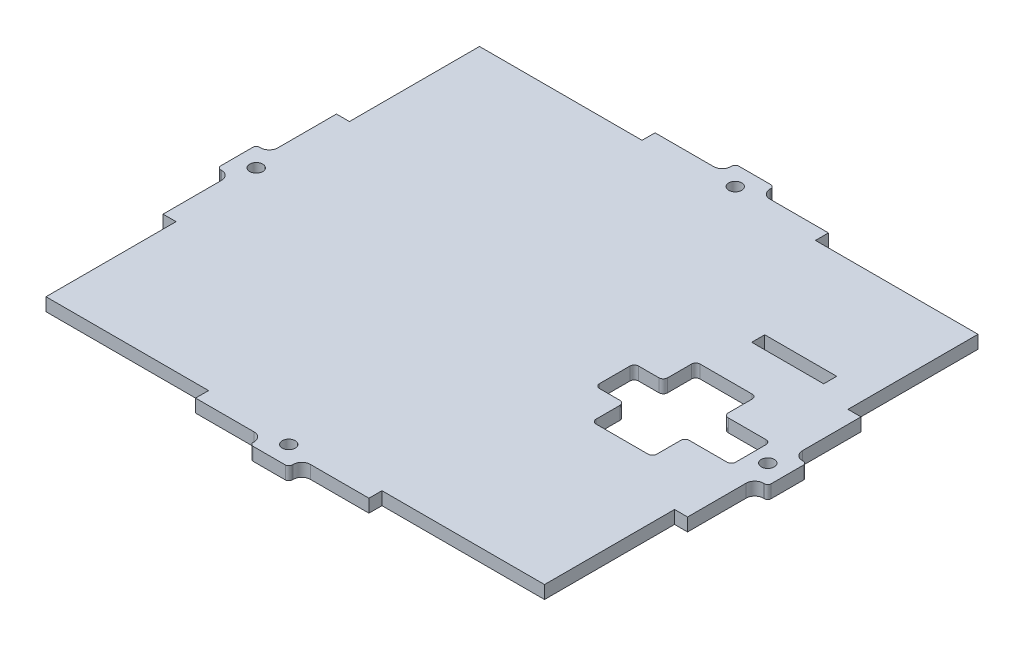
SolidWorks part; units mm, degrees
material "Acrylic (Medium-high impact)"
ref_plane "Plano frontal" through (0, 0, 0) normal (0, 0, 1) x (1, 0, 0)
ref_plane "Plano superior" through (0, 0, 0) normal (0, 1, 0) x (1, 0, 0)
ref_plane "Plano direito" through (0, 0, 0) normal (1, 0, 0) x (0, 0, -1)
sketch "Esboço1" plane through (0, 0, 0) normal (0, 1, 0) x (1, 0, 0)
  line L1 (-57.5, -50) -> (57.5, -50)
  line L2 (-57.5, -50) -> (-57.5, 50)
  line L3 (-57.5, 50) -> (57.5, 50)
  line L4 (57.5, -50) -> (57.5, 50)
  line L5 (-57.5, -50) -> (57.5, 50) construction
  line L6 (-57.5, 50) -> (57.5, -50) construction
  point P0 (0, 0)
  dimension "D1" = 115
  dimension "D2" = 100
extrude "Ressalto-extrusão1" add sketch "Esboço1" along normal mid plane 3
sketch "Esboço4" plane through (0, 1.5, 0) normal (0, 1, 0) x (1, 0, 0)
  line L5 (0, -1.65) -> (0, 1.65) construction
  line L21 (6.5, 53) -> (20, 53)
  line L26 (-3.7, 56) -> (3.7, 56)
  line L27 (-4.5, 55.2) -> (-4.5, 55)
  line L33 (-63.5, 3.7) -> (-63.5, -3.7)
  line L42 (57.5, 50) -> (-57.5, 50) construction
  line L43 (-20, 50) -> (20, 50)
  line L44 (-20, 50) -> (-20, 53)
  line L45 (-20, 53) -> (-6.5, 53)
  line L46 (20, 50) -> (20, 53)
  line L48 (4.5, 55.2) -> (4.5, 55)
  line L49 (-1.65, 0) -> (1.65, 0) construction
  line L50 (4.5, -55.2) -> (4.5, -55)
  line L51 (20, -50) -> (20, -53)
  line L52 (-20, -53) -> (-6.5, -53)
  line L53 (-20, -50) -> (-20, -53)
  line L54 (-20, -50) -> (20, -50)
  line L55 (-4.5, -55.2) -> (-4.5, -55)
  line L56 (-3.7, -56) -> (3.7, -56)
  line L57 (6.5, -53) -> (20, -53)
  line L58 (57.5, -50) -> (57.5, 50) construction
  line L59 (57.5, 20) -> (60.5, 20)
  line L60 (57.5, 20) -> (57.5, -20)
  line L61 (57.5, -20) -> (60.5, -20)
  line L62 (60.5, 20) -> (60.5, 6.5)
  line L63 (60.5, -6.5) -> (60.5, -20)
  line L64 (62.5, 4.5) -> (62.7, 4.5)
  line L66 (62.5, -4.5) -> (62.7, -4.5)
  line L67 (63.5, 3.7) -> (63.5, -3.7)
  line L77 (-62.5, -4.5) -> (-62.7, -4.5)
  line L91 (-62.5, 4.5) -> (-62.7, 4.5)
  line L92 (-60.5, -6.5) -> (-60.5, -20)
  line L93 (-60.5, 20) -> (-60.5, 6.5)
  line L94 (-57.5, -20) -> (-60.5, -20)
  line L95 (-57.5, 20) -> (-57.5, -20)
  line L96 (-57.5, 20) -> (-60.5, 20)
  circle A6 centre (0, 51.5) radius 1.5 construction
  arc A7 (6.5, 53) -> (4.5, 55) centre (6.5, 55) cw
  arc A8 (-4.5, 55) -> (-6.5, 53) centre (-6.5, 55) cw
  circle A9 centre (0, -51.5) radius 1.5 construction
  arc A10 (-4.5, -55) -> (-6.5, -53) centre (-6.5, -55) ccw
  arc A11 (6.5, -53) -> (4.5, -55) centre (6.5, -55) ccw
  arc A12 (60.5, -6.5) -> (62.5, -4.5) centre (62.5, -6.5) cw
  arc A13 (62.5, 4.5) -> (60.5, 6.5) centre (62.5, 6.5) cw
  arc A18 (-62.5, 4.5) -> (-60.5, 6.5) centre (-62.5, 6.5) ccw
  arc A19 (-60.5, -6.5) -> (-62.5, -4.5) centre (-62.5, -6.5) ccw
  arc A20 (-63.5, -3.7) -> (-62.7, -4.5) centre (-62.7, -3.7) ccw
  arc A21 (-63.5, 3.7) -> (-62.7, 4.5) centre (-62.7, 3.7) cw
  arc A22 (-4.5, -55.2) -> (-3.7, -56) centre (-3.7, -55.2) ccw
  arc A23 (4.5, -55.2) -> (3.7, -56) centre (3.7, -55.2) cw
  arc A24 (62.7, -4.5) -> (63.5, -3.7) centre (62.7, -3.7) ccw
  arc A25 (62.7, 4.5) -> (63.5, 3.7) centre (62.7, 3.7) cw
  arc A26 (3.7, 56) -> (4.5, 55.2) centre (3.7, 55.2) cw
  arc A27 (-3.7, 56) -> (-4.5, 55.2) centre (-3.7, 55.2) ccw
  point P16 (63.5, 0)
  point P20 (60.5, 4.5)
  point P21 (57.5, 0)
  point P36 (-60.5, 4.5)
  point P39 (-63.5, -4.5)
  point P42 (0, 50)
  point P51 (4.5, 53)
  point P70 (4.5, -53)
  point P73 (-63.5, 4.5)
  point P76 (-4.5, -56)
  point P79 (4.5, -56)
  point P82 (63.5, -4.5)
  point P85 (63.5, 4.5)
  point P88 (4.5, 56)
  point P91 (-4.5, 56)
  dimension "D2" = 9
  dimension "D6" = 2
  dimension "D8" = 3
  dimension "D9" = 3
  dimension "D11" = 2
  dimension "D7" = 0.8
  dimension "D3" = 40
  dimension "D4" = 9
  dimension "D5" = 3
  dimension "D10" = 3
extrude "Ressalto-extrusão2" add sketch "Esboço4" against normal through all
sketch "Esboço2" plane through (0, 1.5, 0) normal (0, 1, 0) x (1, 0, 0)
  line L27 (0, -1.65) -> (0, 1.65) construction
  line L32 (-20, -53) -> (-6.5, -53) construction
  line L51 (63.5, -3.7) -> (63.5, 3.7) construction
  line L90 (-3.7, -56) -> (3.7, -56) construction
  line L91 (-1.65, 0) -> (1.65, 0) construction
  circle A8 centre (0, -51.5) radius 1.5
  circle A9 centre (0, 51.5) radius 1.5
  circle A11 centre (59, 0) radius 1.5
  circle A14 centre (-59, 0) radius 1.5
  dimension "D1" = 3
  dimension "D2" = 3
  dimension "D3" = 3
extrude "Corte-extrusão1" cut sketch "Esboço2" against normal through all
sketch "Sketch2" plane through (0, 0, 0) normal (0, 1, 0) x (1, 0, 0)
  line L8 (32.2, 2.3) -> (57.5, 2.3) construction
  line L25 (32.2, 28.4) -> (57.5, 28.4) construction
  line L30 (24.7, 4.5) -> (29.4, 4.5)
  line L43 (32.2, 28.4) -> (32.2, -23.8) construction
  line L44 (32.2, -23.8) -> (57.5, -23.8) construction
  line L45 (57.5, 28.4) -> (57.5, -23.8) construction
  line L46 (32.2, -2.3) -> (57.5, -2.3) construction
  line L47 (44.85, 2.3) -> (44.85, -2.3) construction
  line L48 (57.5, 20) -> (57.5, 50) construction
  line L53 (30.4, 5.5) -> (30.4, 11)
  line L54 (33, 25.3) -> (49.6, 25.3)
  line L55 (33, 25.3) -> (33, 22.3)
  line L56 (33, 22.3) -> (49.6, 22.3)
  line L57 (49.6, 25.3) -> (49.6, 22.3)
  line L58 (31.4, 12) -> (43.4, 12)
  line L59 (44.4, 11) -> (44.4, 5.5)
  line L60 (45.4, 4.5) -> (54.1, 4.5)
  line L61 (55.1, 3.5) -> (55.1, -3.5)
  line L62 (54.1, -4.5) -> (45.4, -4.5)
  line L63 (44.4, -5.5) -> (44.4, -11)
  line L64 (43.4, -12) -> (31.4, -12)
  line L65 (30.4, -11) -> (30.4, -5.5)
  line L66 (29.4, -4.5) -> (24.7, -4.5)
  line L67 (23.7, -3.5) -> (23.7, 3.5)
  line L68 (63.5, -3.7) -> (63.5, 3.7) construction
  line L69 (57.5, 50) -> (20, 50) construction
  arc A0 (43.4, 12) -> (44.4, 11) centre (43.4, 11) cw
  arc A1 (44.4, 5.5) -> (45.4, 4.5) centre (45.4, 5.5) ccw
  arc A2 (54.1, 4.5) -> (55.1, 3.5) centre (54.1, 3.5) cw
  arc A3 (55.1, -3.5) -> (54.1, -4.5) centre (54.1, -3.5) cw
  arc A4 (45.4, -4.5) -> (44.4, -5.5) centre (45.4, -5.5) ccw
  arc A5 (44.4, -11) -> (43.4, -12) centre (43.4, -11) cw
  arc A6 (31.4, -12) -> (30.4, -11) centre (31.4, -11) cw
  arc A7 (30.4, -5.5) -> (29.4, -4.5) centre (29.4, -5.5) ccw
  arc A8 (24.7, -4.5) -> (23.7, -3.5) centre (24.7, -3.5) cw
  arc A9 (24.7, 4.5) -> (23.7, 3.5) centre (24.7, 3.5) ccw
  arc A10 (29.4, 4.5) -> (30.4, 5.5) centre (29.4, 5.5) ccw
  arc A11 (30.4, 11) -> (31.4, 12) centre (31.4, 11) cw
  point P10 (44.85, 0)
  point P16 (44.4, 12)
  point P38 (33.46, 12.391)
  point P39 (23.7, 0)
  point P40 (55.4411, 4.385)
  point P41 (46.8516, -5.1394)
  point P45 (44.4, 4.5)
  point P48 (55.1, 4.5)
  point P61 (23.7, -4.5)
  point P64 (23.7, 4.5)
  point P69 (30.4, 12)
  dimension "D10" = 16.6
  dimension "D8" = 1
  dimension "D1" = 52.2
  dimension "D2" = 25.3
  dimension "D4" = 21.5
  dimension "D5" = 7.9
  dimension "D6" = 24.7
  dimension "D7" = 3
  dimension "D9" = 26.1
  dimension "D3" = 4.6
  dimension "D13" = 24
  dimension "D14" = 9
  dimension "D15" = 31.4
  dimension "D16" = 10.7
  dimension "D17" = 14
  dimension "D18" = 8.4
extrude "Cut-Extrude3" cut sketch "Sketch2" against normal through all both and the other way through all
